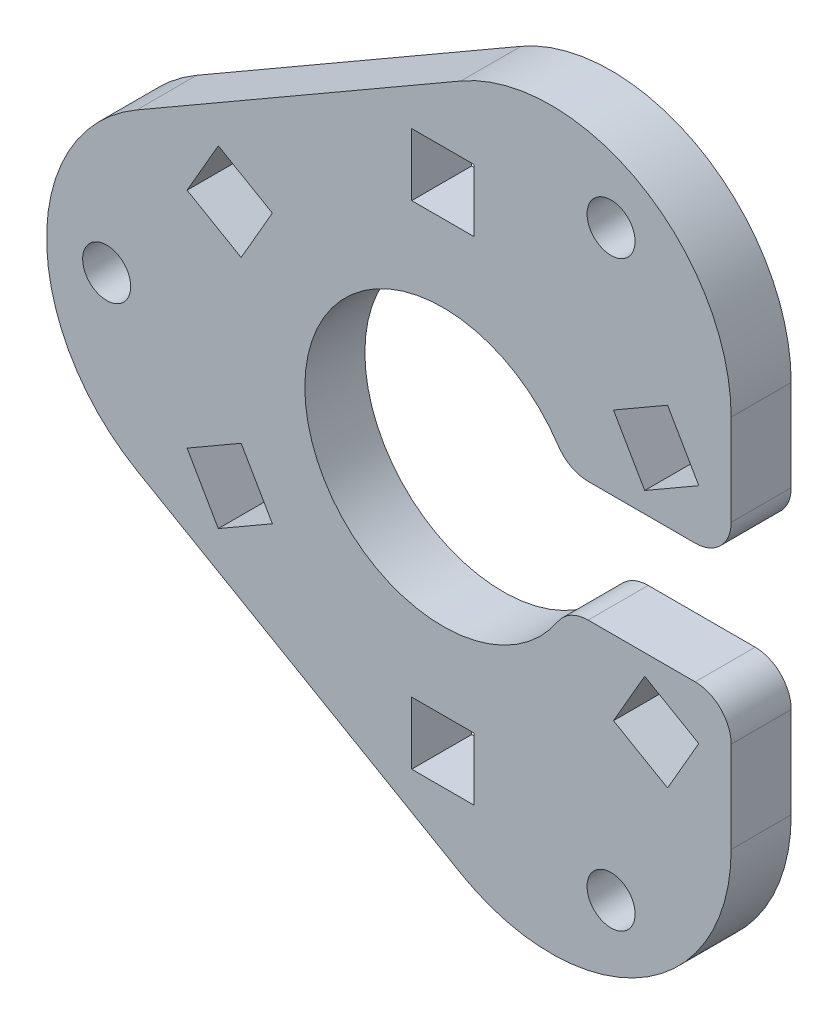
SolidWorks part; units mm, degrees
ref_plane "Front Plane" through (0, 0, 0) normal (0, 0, 1) x (1, 0, 0)
ref_plane "Top Plane" through (0, 0, 0) normal (0, 1, 0) x (1, 0, 0)
ref_plane "Right Plane" through (0, 0, 0) normal (1, 0, 0) x (0, 0, -1)
sketch "Sketch1" plane through (0, 0, 0) normal (0, 0, 1) x (1, 0, 0)
  line L0 (-26, 0) -> (26, 0) construction
  line L7 (-2.6, 23.1) -> (2.6, 23.1)
  line L8 (-2.6, 23.1) -> (-2.6, 17.9)
  line L9 (-2.6, 17.9) -> (2.6, 17.9)
  line L10 (2.6, 23.1) -> (2.6, 17.9)
  line L23 (0, 26) -> (0, -26) construction
  line L24 (21.3052, 9.2983) -> (16.8019, 6.6983)
  line L25 (14.2019, 11.2017) -> (16.8019, 6.6983)
  line L26 (18.7052, 13.8017) -> (14.2019, 11.2017)
  line L27 (18.7052, 13.8017) -> (21.3052, 9.2983)
  line L28 (18.7052, -13.8017) -> (14.2019, -11.2017)
  line L29 (16.8019, -6.6983) -> (14.2019, -11.2017)
  line L30 (21.3052, -9.2983) -> (16.8019, -6.6983)
  line L31 (21.3052, -9.2983) -> (18.7052, -13.8017)
  line L32 (-2.6, -23.1) -> (-2.6, -17.9)
  line L33 (2.6, -17.9) -> (-2.6, -17.9)
  line L34 (2.6, -23.1) -> (2.6, -17.9)
  line L35 (2.6, -23.1) -> (-2.6, -23.1)
  line L36 (-21.3052, -9.2983) -> (-16.8019, -6.6983)
  line L37 (-14.2019, -11.2017) -> (-16.8019, -6.6983)
  line L38 (-18.7052, -13.8017) -> (-14.2019, -11.2017)
  line L39 (-18.7052, -13.8017) -> (-21.3052, -9.2983)
  line L40 (-18.7052, 13.8017) -> (-14.2019, 11.2017)
  line L41 (-16.8019, 6.6983) -> (-14.2019, 11.2017)
  line L42 (-21.3052, 9.2983) -> (-16.8019, 6.6983)
  line L43 (-21.3052, 9.2983) -> (-18.7052, 13.8017)
  line L44 (24, 5) -> (9.815, 5) construction
  line L45 (24, -5) -> (9.815, -5) construction
  line L46 (24, 41.5692) -> (24, -41.5692) construction
  line L47 (24, -41.5692) -> (-48, 0) construction
  line L48 (-48, 0) -> (24, 41.5692) construction
  line L49 (24, 5) -> (24, 41.5692)
  line L50 (24, 41.5692) -> (-48, 0)
  line L51 (-48, 0) -> (24, -41.5692)
  line L52 (24, -41.5692) -> (24, -5)
  line L53 (0, 0) -> (24, 41.5692) construction
  line L54 (-2.6, 20.5) -> (2.6, 20.5) construction
  line L55 (6.3509, 11) -> (9.815, 5) construction
  line L56 (6.3509, -11) -> (12.7017, 0) construction
  line L57 (12.7017, 0) -> (6.3509, 11) construction
  line L58 (6.3509, 11) -> (-6.3509, 11) construction
  line L59 (-6.3509, 11) -> (-12.7017, 0) construction
  line L60 (-12.7017, 0) -> (-6.3509, -11) construction
  line L61 (-6.3509, -11) -> (6.3509, -11) construction
  line L62 (9.815, -5) -> (6.3509, -11) construction
  line L63 (10.3562, 5) -> (24, 5)
  line L64 (10.3562, -5) -> (24, -5)
  circle A0 centre (0, 0) radius 13.75 construction
  circle A4 centre (14, 24.2487) radius 2
  circle A5 centre (14, -24.2487) radius 2
  circle A6 centre (-28, 0) radius 2
  circle A7 centre (0, 0) radius 11 construction
  arc A8 (10.3562, 5) -> (10.3562, -5) centre (0, 0) ccw
  point P40 (0, 0)
  point P48 (0, 0)
  point P50 (0, 0)
  dimension "D2" = 24
  dimension "D1" = 27.5
  dimension "D10" = 4
  dimension "D14" = 11.5
  dimension "D3" = 5.2
  dimension "D4" = 5.2
  dimension "D5" = 20.5
  dimension "D6" = 6
  dimension "D7" = 10
  dimension "D9" = 28
  dimension "D11" = 3
  dimension "D12" = 22
  dimension "D13" = 17.9
  dimension "D8" = 3
extrude "Boss-Extrude1" add sketch "Sketch1" along normal blind 5
fillet "Congé1" radius 15 3 edges at (24, -41.5692, 2.5) (-48, 0, 2.5) (24, 41.5692, 2.5)
fillet "Congé2" radius 3 4 edges at (10.3562, -5, 2.5) (10.3562, 5, 2.5) (24, -5, 2.5) (24, 5, 2.5)
sketch "Esquisse1" plane through (0, 0, 5) normal (0, 0, 1) x (1, 0, 0)
  circle A0 centre (0, 0) radius 33 construction
  arc A1 (24, 15.5885) -> (1.5, 28.5788) centre (9, 15.5885) ccw construction
